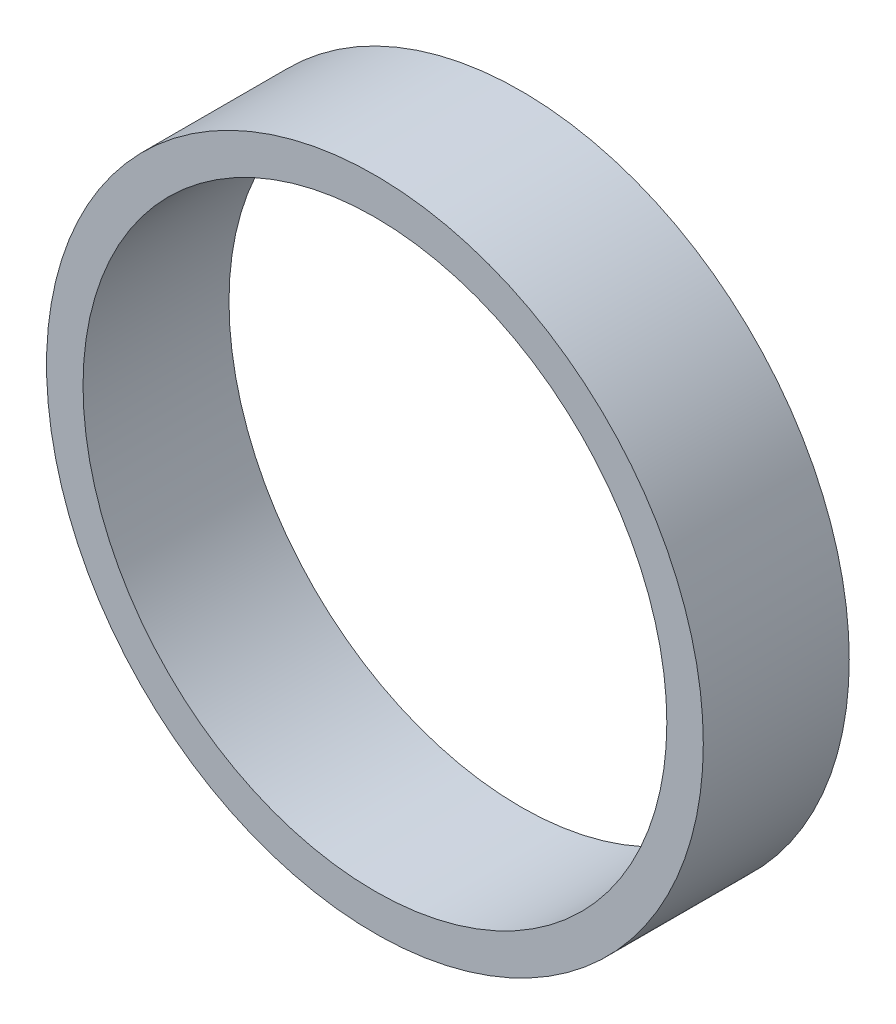
SolidWorks part; units mm, degrees
material "6061 Alloy"
ref_plane "Front Plane" through (0, 0, 0) normal (0, 0, 1) x (1, 0, 0)
ref_plane "Top Plane" through (0, 0, 0) normal (0, 1, 0) x (1, 0, 0)
ref_plane "Right Plane" through (0, 0, 0) normal (1, 0, 0) x (0, 0, -1)
sketch "Sketch1" plane through (0, 0, 0) normal (0, 0, 1) x (1, 0, 0)
  circle A0 centre (0, 0) radius 50.8
  circle A1 centre (0, 0) radius 57.15
extrude "Boss-Extrude1" add sketch "Sketch1" along normal blind 25.4
